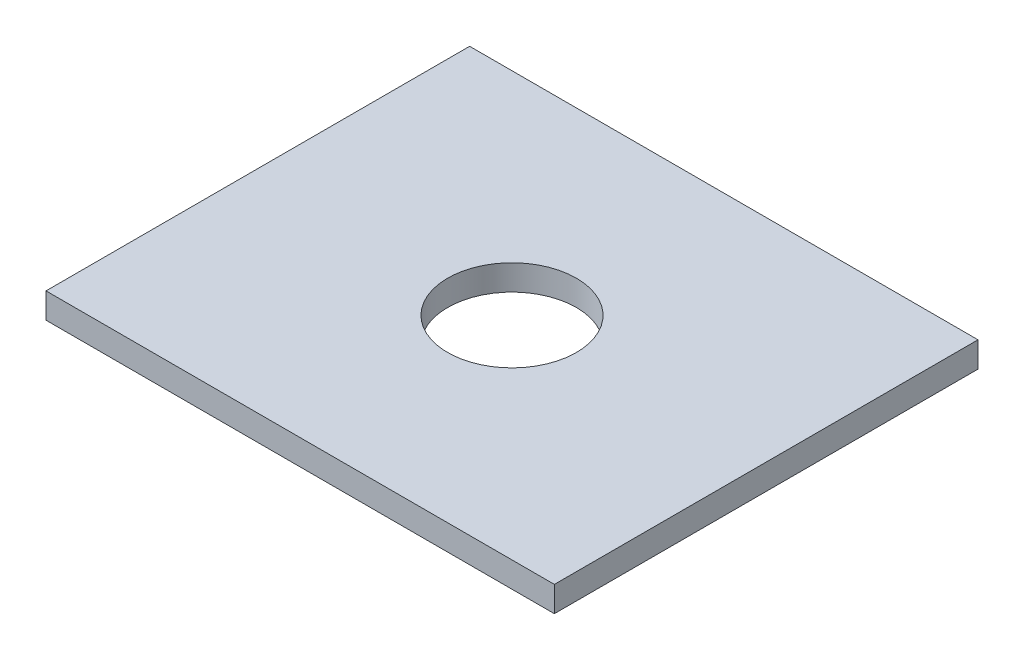
SolidWorks part; units mm, degrees
material "Gray Cast Iron"
ref_plane "Front Plane" through (0, 0, 0) normal (0, 0, 1) x (1, 0, 0)
ref_plane "Top Plane" through (0, 0, 0) normal (0, 1, 0) x (1, 0, 0)
ref_plane "Right Plane" through (0, 0, 0) normal (1, 0, 0) x (0, 0, -1)
sketch "Sketch1" plane through (0, 0, 0) normal (0, 1, 0) x (1, 0, 0)
  line L1 (150, -125) -> (-150, -125)
  line L2 (150, -125) -> (150, 125)
  line L3 (150, 125) -> (-150, 125)
  line L4 (-150, -125) -> (-150, 125)
  line L5 (150, -125) -> (-150, 125) construction
  line L6 (150, 125) -> (-150, -125) construction
  point P0 (0, 0)
  dimension "D1" = 300
  dimension "D2" = 250
extrude "Boss-Extrude1" add sketch "Sketch1" against normal blind 15
sketch "Sketch3" plane through (0, -15, 0) normal (0, -1, 0) x (-1, 0, 0)
  circle A0 centre (0, 0) radius 38
  dimension "D1" = 76
extrude "Cut-Extrude1" cut sketch "Sketch3" against normal blind 15
sketch "Sketch4" [suppressed] plane through (0, 5, 0) normal (0, 1, 0) x (1, 0, 0)
  circle A0 centre (0, 0) radius 25
  dimension "D1" = 50
extrude "Cut-Extrude2" [suppressed] cut sketch "Sketch4" against normal blind 10
sketch3d "3DSketch1"
  point P0 (0, 15, 0)
sketch3d "3DSketch2"
  point P0 (0, 0, 0)
